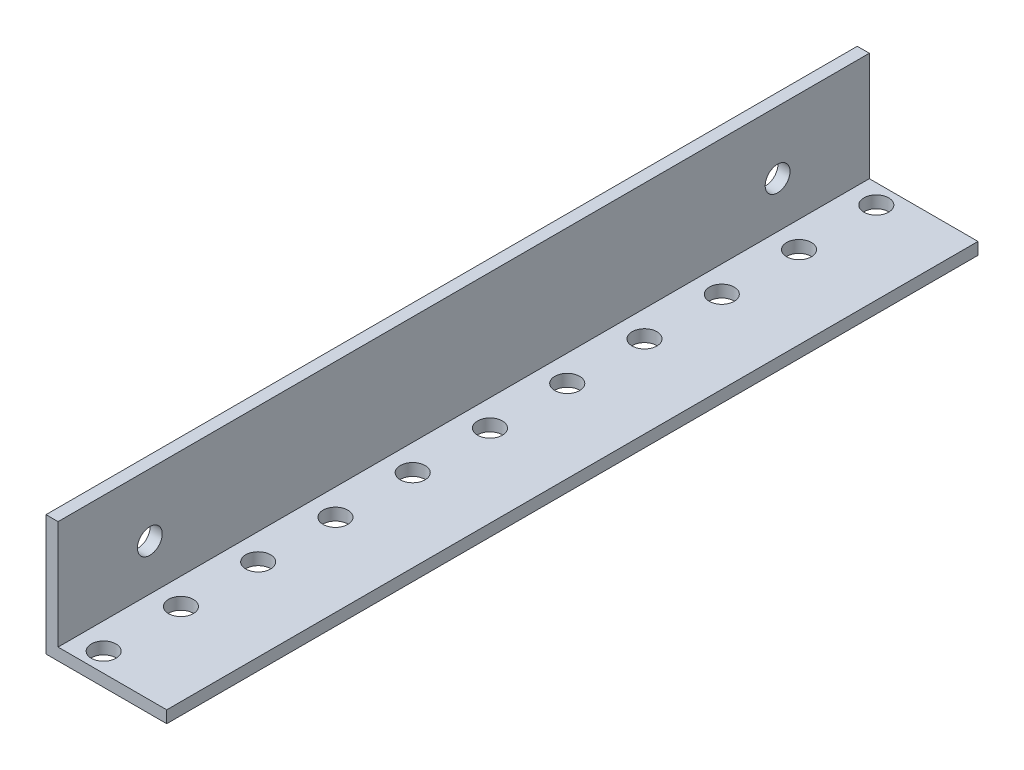
SolidWorks part; units mm, degrees
material "6061-T6 (SS)"
ref_plane "Front Plane" through (0, 0, 0) normal (0, 0, 1) x (1, 0, 0)
ref_plane "Top Plane" through (0, 0, 0) normal (0, 1, 0) x (1, 0, 0)
ref_plane "Right Plane" through (0, 0, 0) normal (1, 0, 0) x (0, 0, -1)
sketch "Sketch1" plane through (0, 0, 0) normal (0, 0, 1) x (1, 0, 0)
  line L0 (0, 0) -> (0, 15.875)
  line L1 (0, 15.875) -> (1.5875, 15.875)
  line L2 (1.5875, 15.875) -> (1.5875, 1.5875)
  line L3 (1.5875, 1.5875) -> (15.875, 1.5875)
  line L4 (15.875, 1.5875) -> (15.875, 0)
  line L5 (15.875, 0) -> (0, 0)
  dimension "D1" = 15.875
  dimension "D2" = 1.5875
  dimension "D3" = 15.875
extrude "Extrude1" add sketch "Sketch1" along normal mid plane 106.68
sketch "Sketch2" plane through (0, 1.5875, 0) normal (0, 1, 0) x (1, 0, 0)
  line L0 (15.875, 0) -> (5.0419, 0) construction
  line L1 (5.0419, 0) -> (1.5875, 0) construction
  line L5 (1.5875, -53.34) -> (1.5875, 53.34) construction
  point P6 (7.1437, 0)
  dimension "D1" = 3.4544
hole_wizard "#4 Clearance Hole1" positions "3DSketch1" profile "Sketch3" hole size "#4" standard "Ansi Inch"
sketch3d "3DSketch1"
  point P4 (5.0419, 1.5875, 0)
sketch "Sketch3" plane through (5.0419, 1.5875, 0) normal (1, 0, 0) x (0, 0, 1)
  line L0 (0, 0) -> (0, 16.2206)
  line L1 (0, 16.2206) -> (1.6319, 15.24)
  line L2 (1.6319, 15.24) -> (1.6319, 0)
  line L5 (1.6319, 0) -> (0, 0)
  line L10 (0, 16.2206) -> (-1.6319, 15.24) construction
  line L11 (0, -6.35) -> (0, 107.95) construction
  dimension "Hole Dia." = 3.2639
  dimension "Hole Depth" = 15.24
  dimension "Drill Angle" = 118
pattern_linear "LPattern1" count 6 spacing 10.16 along (0, 0, 1) count 6 spacing 10.16 along (0, 0, -1) of "#4 Clearance Hole1"
sketch "Sketch4" plane through (1.5875, 0, 0) normal (1, 0, 0) x (0, 0, -1)
  line L0 (41.275, 1.5875) -> (41.275, 7.6403) construction
  line L1 (-41.275, 1.5875) -> (-41.275, 7.6403) construction
  line L2 (-53.34, 1.5875) -> (53.34, 1.5875) construction
  line L3 (41.275, 7.6403) -> (0, 7.6403) construction
  line L4 (0, 7.6403) -> (-41.275, 7.6403) construction
  line L5 (0, 7.6403) -> (0, 1.5875) construction
  point P6 (-63.5, 7.1437)
  dimension "D1" = 41.275
  dimension "D2" = 6.0528
hole_wizard "#4 Clearance Hole2" positions "3DSketch2" profile "Sketch5" hole size "#4" standard "Ansi Inch"
sketch3d "3DSketch2"
  point P9 (1.5875, 7.6403, -41.275)
  point P13 (1.5875, 7.6403, 41.275)
sketch "Sketch5" plane through (1.5875, 7.6403, -41.275) normal (0, 1, 0) x (0, 0, -1)
  line L0 (0, 0) -> (0, 16.2206)
  line L1 (0, 16.2206) -> (1.6319, 15.24)
  line L2 (1.6319, 15.24) -> (1.6319, 0)
  line L5 (1.6319, 0) -> (0, 0)
  line L10 (0, 16.2206) -> (-1.6319, 15.24) construction
  line L11 (0, -6.35) -> (0, 107.95) construction
  dimension "Hole Dia." = 3.2639
  dimension "Hole Depth" = 15.24
  dimension "Drill Angle" = 118
chamfer "Chamfer1" [suppressed] distance 10.16 angle 45
